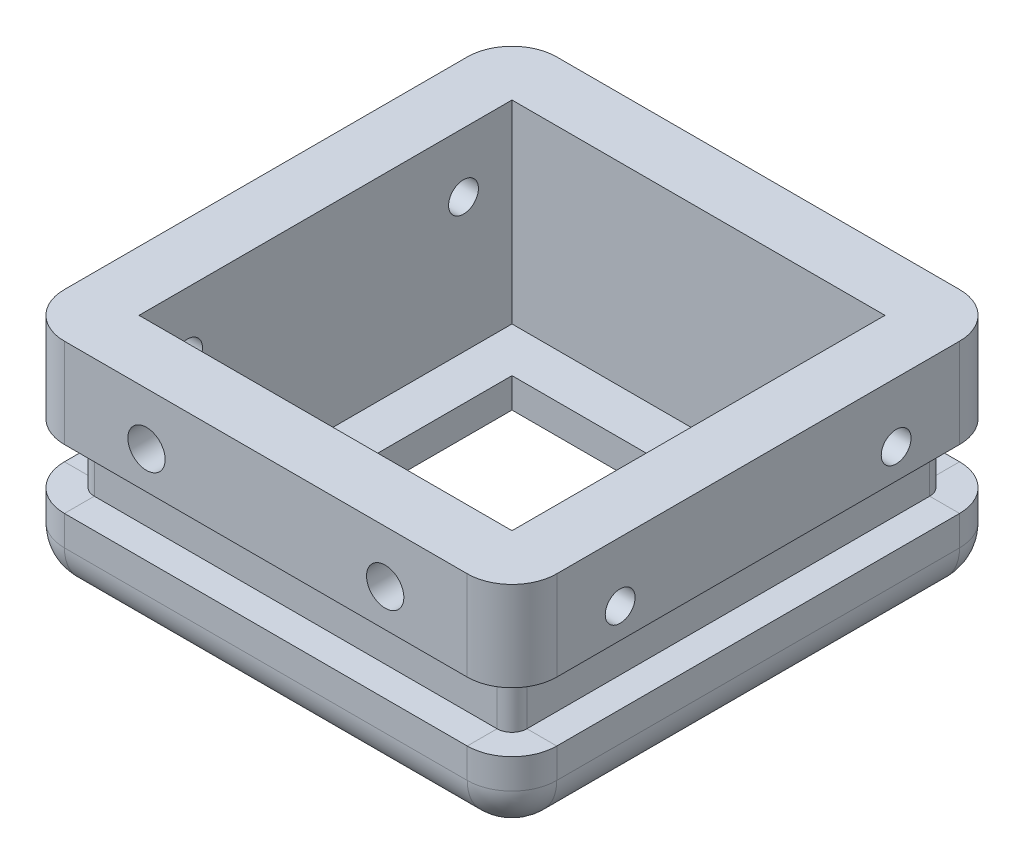
SolidWorks part; units mm, degrees
material "PBT Общее назначение"
ref_plane "Спереди" through (0, 0, 0) normal (0, 0, 1) x (1, 0, 0)
ref_plane "Сверху" through (0, 0, 0) normal (0, 1, 0) x (1, 0, 0)
ref_plane "Справа" through (0, 0, 0) normal (1, 0, 0) x (0, 0, -1)
sketch "Эскиз1" plane through (0, 0, 0) normal (0, 1, 0) x (1, 0, 0)
  line L0 (0, 0) -> (13, 0)
  line L1 (0, 0) -> (0, 13)
  line L2 (13, 0) -> (13, 13)
  line L3 (0, 13) -> (13, 13)
  line L4 (-10, 23) -> (23, 23)
  line L5 (-10, 23) -> (-10, -10)
  line L6 (23, 23) -> (23, -10)
  line L7 (-10, -10) -> (23, -10)
  line L8 (6.5, 23) -> (6.5, -10) construction
  line L9 (23, 6.5) -> (-10, 6.5) construction
  line L10 (6.5, 13) -> (6.5, 0) construction
  line L11 (13, 6.5) -> (0, 6.5) construction
  dimension "D1" = 13
  dimension "D2" = 13
  dimension "D3" = 33
  dimension "D4" = 33
extrude "Бобышка-Вытянуть1" add sketch "Эскиз1" along normal blind 15
sketch "Эскиз2" plane through (0, 15, 0) normal (0, 1, 0) x (1, 0, 0)
  line L0 (-6, 19) -> (19, 19)
  line L1 (-6, 19) -> (-6, -6)
  line L2 (19, 19) -> (19, -6)
  line L3 (-6, -6) -> (19, -6)
  line L4 (19, 6.5) -> (-6, 6.5) construction
  line L5 (6.5, 19) -> (6.5, -6) construction
  line L6 (13, 13) -> (0, 13) construction
  line L7 (13, 0) -> (13, 13) construction
  point P8 (6.5, 13)
  point P9 (13, 6.5)
  dimension "D1" = 25
  dimension "D2" = 25
extrude "Вырез-Вытянуть1" cut sketch "Эскиз2" against normal blind 13
fillet "Скругление3" radius 3 8 edges at (-10, 7.5, -23) (-10, 7.5, 10) (-10, 0, -6.5) (6.5, 0, -23) (23, 7.5, -23) (23, 0, -6.5) (23, 7.5, 10) (6.5, 0, 10)
sketch "Эскиз3" plane through (-10, 0, 0) normal (-1, 0, 0) x (0, 0, 1)
  circle A0 centre (2.75, 10) radius 1 construction
  circle A1 centre (2.75, 10) radius 1 construction
  circle A2 centre (-15.75, 10) radius 1 construction
  circle A3 centre (-15.75, 10) radius 1 construction
sketch "Эскиз4" plane through (-10, 0, 0) normal (-1, 0, 0) x (0, 0, 1)
  line L0 (2.75, 10) -> (2.75, 7.0387) construction
  line L1 (-15.75, 10) -> (-15.75, 7.0387) construction
  line L2 (-20, 15) -> (7, 15) construction
  line L3 (2.75, 11) -> (-15.75, 11) construction
  circle A0 centre (2.75, 11) radius 1
  circle A1 centre (-15.75, 11) radius 1
  dimension "D1" = 4
  dimension "D3" = 2
  dimension "D4" = 2
extrude "Вырез-Вытянуть2" cut sketch "Эскиз4" against normal through all
sketch "Эскиз11" plane through (0, 0, 0) normal (0, -1, 0) x (1, 0, 0)
  line L0 (16, 3) -> (16, -16)
  line L1 (16, 3) -> (-3, 3)
  line L2 (16, -16) -> (-3, -16)
  line L3 (-3, 3) -> (-3, -16)
  line L4 (13, 0) -> (13, -13) construction
  line L5 (13, -13) -> (0, -13) construction
  line L6 (0, 0) -> (13, 0) construction
  line L7 (0, -13) -> (0, 0) construction
  dimension "D1" = 3
  dimension "D2" = 3
  dimension "D3" = 3
  dimension "D4" = 3
extrude "Вырез-Вытянуть5" cut sketch "Эскиз11" against normal up to surface (2 mm away) up to face at (6.5, 2, -6.5)
ref_plane "Плоскость2" through (-7, 0, 0) normal (-1, 0, 0) x (0, 1, 0)
sketch "Эскиз14" plane through (-7, 0, 0) normal (-1, 0, 0) x (0, 1, 0)
  line L0 (11, -2.75) -> (11, 15.75) construction
  line L1 (5, 23) -> (9, 23)
  line L2 (5, 23) -> (5, 21)
  line L3 (9, 23) -> (9, 21)
  line L4 (5, 21) -> (9, 21)
  line L6 (3, 23) -> (15, 23) construction
  line L7 (7, 23) -> (7, 21) construction
  circle A0 centre (11, 15.75) radius 1 construction
  circle A1 centre (11, -2.75) radius 1 construction
  circle A2 centre (11, 15.75) radius 1 construction
  circle A3 centre (11, -2.75) radius 1 construction
  dimension "D1" = 2
  dimension "D2" = 4
  dimension "D3" = 2
ref_plane "Плоскость4" through (0, 7, 0) normal (0, -1, 0) x (0, 0, 1)
sketch "Эскиз16" plane through (0, 7, 0) normal (0, -1, 0) x (0, 0, 1)
  line L4 (-23, 7) -> (-23, -20)
  line L5 (7, 10) -> (-20, 10)
  line L6 (10, -20) -> (10, 7)
  line L7 (-20, -23) -> (7, -23)
  line L8 (-23, 7) -> (-23, -20)
  line L9 (7, 10) -> (-20, 10)
  line L10 (10, -20) -> (10, 7)
  line L11 (-20, -23) -> (7, -23)
  arc A4 (-20, 10) -> (-23, 7) centre (-20, 7) ccw
  arc A5 (10, 7) -> (7, 10) centre (7, 7) ccw
  arc A6 (7, -23) -> (10, -20) centre (7, -20) ccw
  arc A7 (-23, -20) -> (-20, -23) centre (-20, -20) ccw
  arc A8 (-20, 10) -> (-23, 7) centre (-20, 7) ccw
  arc A9 (10, 7) -> (7, 10) centre (7, 7) ccw
  arc A10 (7, -23) -> (10, -20) centre (7, -20) ccw
  arc A11 (-23, -20) -> (-20, -23) centre (-20, -20) ccw
  dimension "D1" = 0
sweep "Вырез-По траектории2" cut profiles "Эскиз14" path "Эскиз16"
sketch "Эскиз17" plane through (0, 0, 10) normal (0, 0, 1) x (1, 0, 0)
  line L0 (14.5, 11.5) -> (-1.5, 11.5) construction
  line L1 (14.5, 11.5) -> (14.5, 9.1906) construction
  line L2 (14.5, 9.1906) -> (16.5, 10.3453)
  line L3 (16.5, 10.3453) -> (16.5, 12.6547)
  line L4 (16.5, 12.6547) -> (14.5, 13.8094)
  line L5 (14.5, 13.8094) -> (12.5, 12.6547)
  line L6 (12.5, 12.6547) -> (12.5, 10.3453)
  line L7 (12.5, 10.3453) -> (14.5, 9.1906)
  line L8 (-1.5, 9.1906) -> (0.5, 10.3453)
  line L9 (0.5, 10.3453) -> (0.5, 12.6547)
  line L10 (0.5, 12.6547) -> (-1.5, 13.8094)
  line L11 (-1.5, 13.8094) -> (-3.5, 12.6547)
  line L12 (-3.5, 12.6547) -> (-3.5, 10.3453)
  line L13 (-3.5, 10.3453) -> (-1.5, 9.1906)
  line L14 (-1.5, 11.5) -> (-1.5, 9.1906) construction
  line L15 (-7, 15) -> (20, 15) construction
  line L16 (6.5, 9) -> (6.5, 15) construction
  line L17 (20, 9) -> (-7, 9) construction
  circle A0 centre (14.5, 11.5) radius 2 construction
  circle A1 centre (-1.5, 11.5) radius 2 construction
  point P22 (6.5, 11.5)
  dimension "D1" = 16
  dimension "D2" = 3.5
  dimension "D3" = 4
  dimension "D4" = 4
sketch "Эскиз18" plane through (0, 0, 6) normal (0, 0, -1) x (-1, 0, 0)
  line L6 (-0.5, 10.3453) -> (1.5, 9.1906)
  line L7 (-0.5, 12.6547) -> (-0.5, 10.3453)
  line L8 (1.5, 13.8094) -> (-0.5, 12.6547)
  line L9 (3.5, 12.6547) -> (1.5, 13.8094)
  line L10 (3.5, 10.3453) -> (3.5, 12.6547)
  line L11 (1.5, 9.1906) -> (3.5, 10.3453)
  line L12 (-0.5, 10.3453) -> (1.5, 9.1906)
  line L13 (-0.5, 12.6547) -> (-0.5, 10.3453)
  line L14 (1.5, 13.8094) -> (-0.5, 12.6547)
  line L15 (3.5, 12.6547) -> (1.5, 13.8094)
  line L16 (3.5, 10.3453) -> (3.5, 12.6547)
  line L17 (1.5, 9.1906) -> (3.5, 10.3453)
  line L18 (-16.5, 10.3453) -> (-14.5, 9.1906)
  line L19 (-16.5, 12.6547) -> (-16.5, 10.3453)
  line L20 (-14.5, 13.8094) -> (-16.5, 12.6547)
  line L21 (-12.5, 12.6547) -> (-14.5, 13.8094)
  line L22 (-12.5, 10.3453) -> (-12.5, 12.6547)
  line L23 (-14.5, 9.1906) -> (-12.5, 10.3453)
  line L24 (-16.5, 10.3453) -> (-14.5, 9.1906)
  line L25 (-16.5, 12.6547) -> (-16.5, 10.3453)
  line L26 (-14.5, 13.8094) -> (-16.5, 12.6547)
  line L27 (-12.5, 12.6547) -> (-14.5, 13.8094)
  line L28 (-12.5, 10.3453) -> (-12.5, 12.6547)
  line L29 (-14.5, 9.1906) -> (-12.5, 10.3453)
  dimension "D1" = 0
  dimension "D2" = 0
extrude "Вырез-Вытянуть6" cut sketch "Эскиз18" against normal blind 2
sketch "Эскиз20" plane through (0, 0, 8) normal (0, 0, -1) x (-1, 0, 0)
  line L0 (-14.5, 9.1906) -> (-14.5, 13.8094) construction
  line L1 (1.5, 13.8094) -> (1.5, 9.1906) construction
  circle A0 centre (-14.5, 11.5) radius 1.25
  circle A1 centre (1.5, 11.5) radius 1.25
  dimension "D1" = 2.5
  dimension "D2" = 2.5
extrude "Вырез-Вытянуть7" cut sketch "Эскиз20" against normal through all
sketch "Эскиз21" plane through (-7, 0, 0) normal (-1, 0, 0) x (0, 1, 0)
  line L0 (9, 23) -> (5, 23)
  line L1 (5, 23) -> (5, 22.2)
  line L2 (5, 22.2) -> (9, 22.8)
  line L3 (9, 22.8) -> (9, 23)
  line L4 (9, 21) -> (9, 23) construction
  line L5 (9, 21) -> (9, 23) construction
  line L6 (5, 23) -> (5, 21) construction
  dimension "D1" = 0.2
  dimension "D2" = 0.8
sketch "Эскиз22" plane through (0, 9, 0) normal (0, -1, 0) x (1, 0, 0)
  line L0 (20, 10) -> (-7, 10) construction
  line L1 (20, 10) -> (-7, 10)
  line L2 (-10, 7) -> (-10, -20) construction
  line L3 (20, -23) -> (-7, -23) construction
  line L4 (-10, 7) -> (-10, -20)
  line L5 (20, -23) -> (-7, -23)
  line L6 (23, -20) -> (23, 7) construction
  line L7 (23, -20) -> (23, 7)
  arc A0 (-7, 10) -> (-10, 7) centre (-7, 7) ccw construction
  arc A1 (-7, 10) -> (-10, 7) centre (-7, 7) ccw
  arc A2 (-10, -20) -> (-7, -23) centre (-7, -20) ccw construction
  arc A3 (-10, -20) -> (-7, -23) centre (-7, -20) ccw
  arc A4 (20, -23) -> (23, -20) centre (20, -20) ccw construction
  arc A5 (20, -23) -> (23, -20) centre (20, -20) ccw
  arc A6 (23, 7) -> (20, 10) centre (20, 7) ccw construction
  arc A7 (23, 7) -> (20, 10) centre (20, 7) ccw
